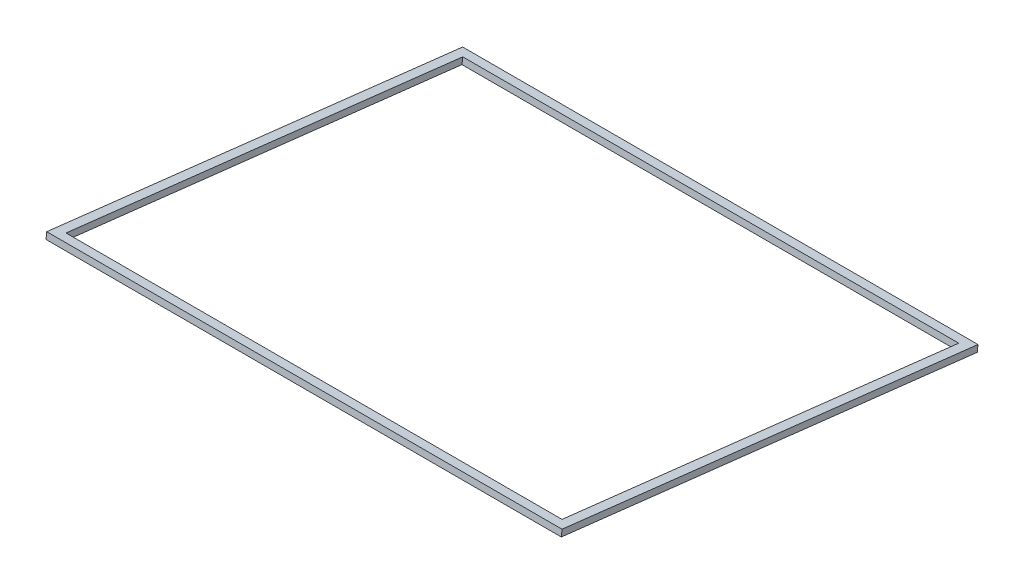
SolidWorks part; units mm, degrees
material "Rubber"
ref_plane "Front Plane" through (0, 0, 0) normal (0, 0, 1) x (1, 0, 0)
ref_plane "Top Plane" through (0, 0, 0) normal (0, 1, 0) x (1, 0, 0)
ref_plane "Right Plane" through (0, 0, 0) normal (1, 0, 0) x (0, 0, -1)
sketch "Sketch1" plane through (0, 358.8799, -41.4225) normal (0, 0.9934, -0.1147) x (1, 0, 0)
  line L148 (-215, 85.2443) -> (-55, 85.2443)
  line L149 (-55, 85.2443) -> (-55, 215.2443)
  line L150 (-55, 215.2443) -> (-215, 215.2443)
  line L151 (-215, 215.2443) -> (-215, 85.2443)
  line L152 (-215, 85.2443) -> (-55, 85.2443)
  line L153 (-55, 85.2443) -> (-55, 215.2443)
  line L154 (-55, 215.2443) -> (-215, 215.2443)
  line L155 (-215, 215.2443) -> (-215, 85.2443)
  line L156 (-212, 88.2443) -> (-58, 88.2443)
  line L157 (-58, 88.2443) -> (-58, 212.2443)
  line L158 (-58, 212.2443) -> (-212, 212.2443)
  line L159 (-212, 212.2443) -> (-212, 88.2443)
  line L160 (-212, 88.2443) -> (-58, 88.2443)
  line L161 (-58, 88.2443) -> (-58, 212.2443)
  line L162 (-58, 212.2443) -> (-212, 212.2443)
  line L163 (-212, 212.2443) -> (-212, 88.2443)
  dimension "D1" = 0
  dimension "D2" = 0
extrude "Boss-Extrude1" add sketch "Sketch1" against normal up to vertex from vertex
